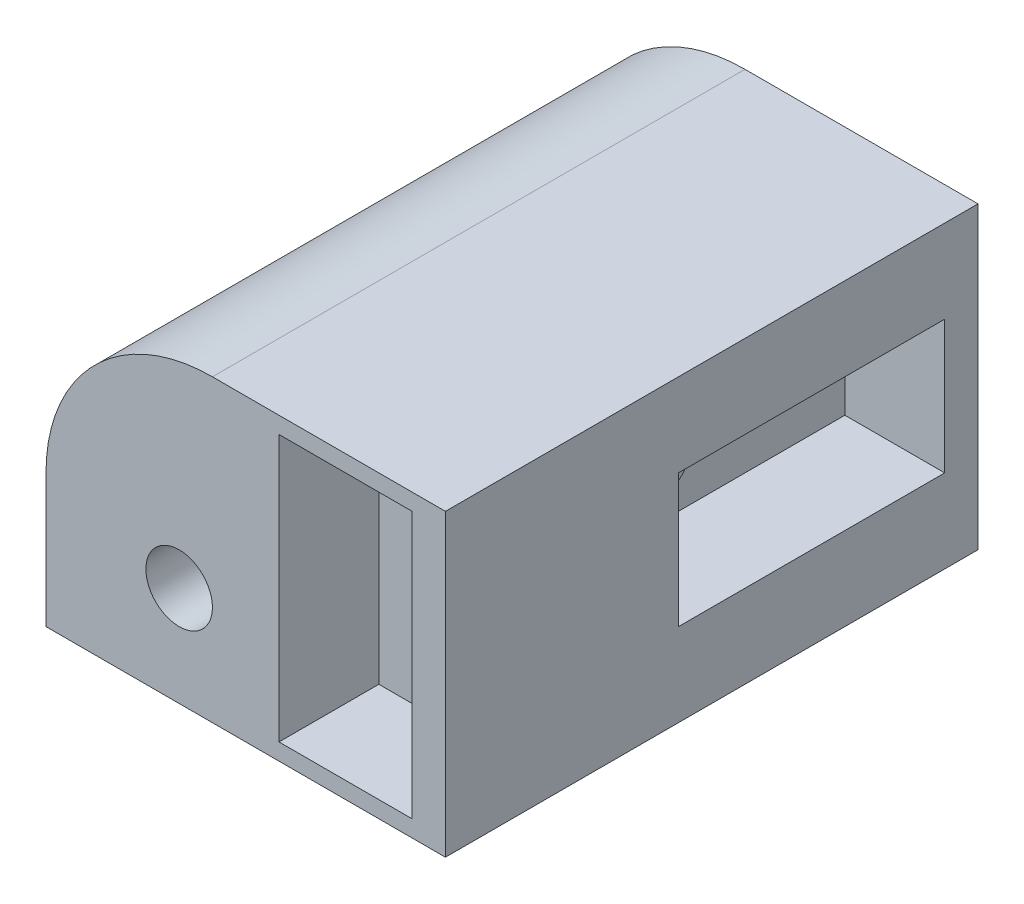
SolidWorks part; units mm, degrees
ref_plane "Front Plane" through (0, 0, 0) normal (0, 0, 1) x (1, 0, 0)
ref_plane "Top Plane" through (0, 0, 0) normal (0, 1, 0) x (1, 0, 0)
ref_plane "Right Plane" through (0, 0, 0) normal (1, 0, 0) x (0, 0, -1)
sketch "Sketch1" plane through (0, 0, 0) normal (0, 0, 1) x (1, 0, 0)
  line L1 (-17.631, 38.4488) -> (58.569, 38.4488)
  line L2 (-17.631, 38.4488) -> (-17.631, -18.7012)
  line L3 (-17.631, -18.7012) -> (58.569, -18.7012)
  line L4 (58.569, 38.4488) -> (58.569, -18.7012)
  circle A0 centre (7.769, 0.3488) radius 6.35
  dimension "D3" = 50.8
  dimension "D4" = 19.05
  dimension "D1" = 76.2
  dimension "D2" = 57.15
extrude "Boss-Extrude1" add sketch "Sketch1" along normal blind 101.6
sketch "Sketch2" plane through (58.569, 0, 0) normal (-1, 0, 0) x (0, 0, 1)
  line L0 (0, 38.4488) -> (0, -18.7012) construction
  line L1 (6.35, 22.5738) -> (57.15, 22.5738)
  line L2 (6.35, 22.5738) -> (6.35, -2.8262)
  line L3 (6.35, -2.8262) -> (57.15, -2.8262)
  line L4 (57.15, 22.5738) -> (57.15, -2.8262)
  line L5 (101.6, -18.7012) -> (0, -18.7012) construction
  dimension "D1" = 50.8
  dimension "D2" = 6.35
  dimension "D3" = 25.4
  dimension "D4" = 15.875
extrude "Cut-Extrude1" cut sketch "Sketch2" along normal blind 19.05
sketch "Sketch3" plane through (0, 0, 101.6) normal (0, 0, 1) x (1, 0, 0)
  line L0 (-17.631, -18.7012) -> (58.569, -18.7012) construction
  line L1 (26.819, 35.2738) -> (52.219, 35.2738)
  line L2 (26.819, 35.2738) -> (26.819, -15.5262)
  line L3 (26.819, -15.5262) -> (52.219, -15.5262)
  line L4 (52.219, 35.2738) -> (52.219, -15.5262)
  line L6 (58.569, -18.7012) -> (58.569, 38.4488) construction
  dimension "D1" = 25.4
  dimension "D2" = 50.8
  dimension "D3" = 3.175
  dimension "D4" = 6.35
extrude "Cut-Extrude2" cut sketch "Sketch3" against normal blind 19.05
sketch "Sketch4" plane through (39.519, 0, 0) normal (1, 0, 0) x (0, 0, -1)
  line L0 (-57.15, -2.8262) -> (-57.15, 22.5738) construction
  line L1 (-57.15, 22.5738) -> (-6.35, 22.5738) construction
  circle A0 centre (-44.45, 9.8738) radius 6.35
  dimension "D1" = 12.7
  dimension "D3" = 12.7
  dimension "D2" = 12.7
extrude "Boss-Extrude2" add sketch "Sketch4" along normal blind 2.54
fillet "Fillet1" radius 31.75 1 edges at (-17.631, 38.4488, 50.8)
